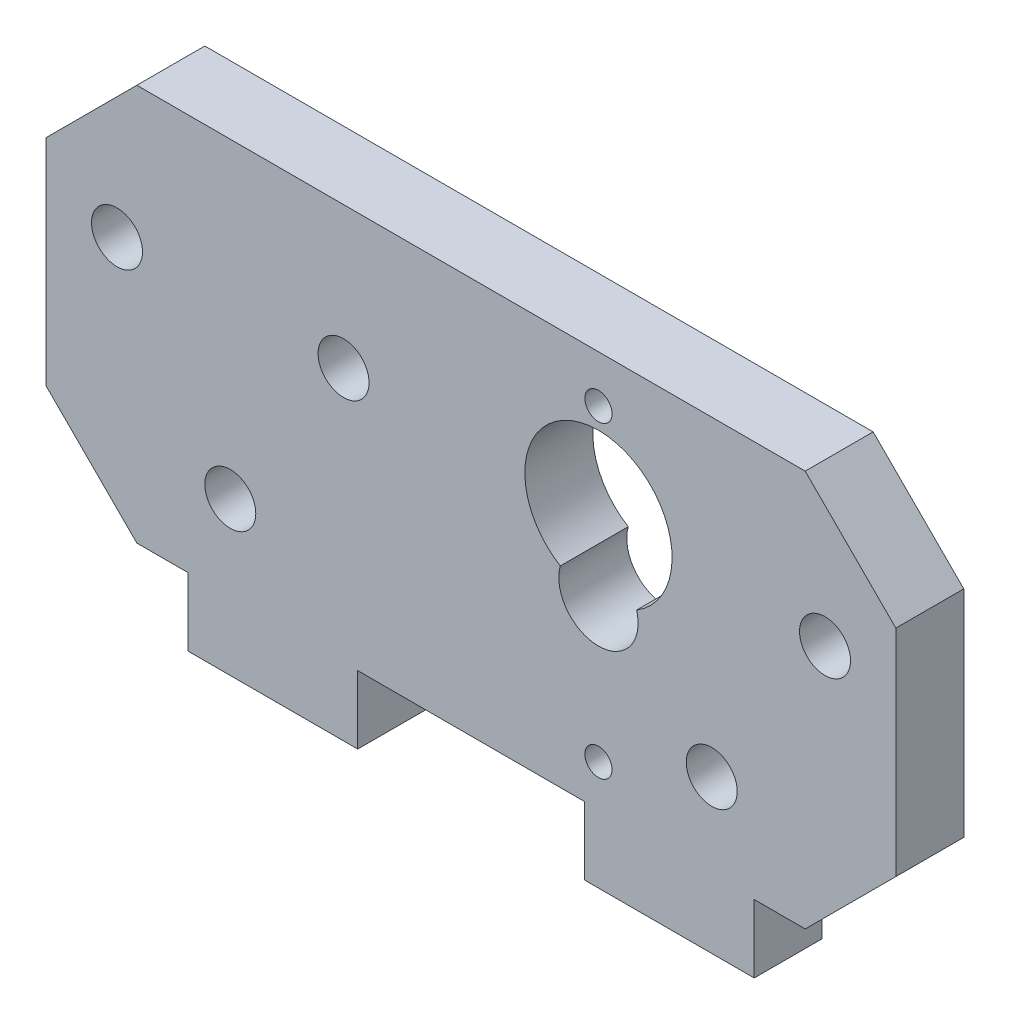
SolidWorks part; units mm, degrees
material "6061-T6 (SS)"
ref_plane "Alzado" through (0, 0, 0) normal (0, 0, 1) x (1, 0, 0)
ref_plane "Planta" through (0, 0, 0) normal (0, 1, 0) x (1, 0, 0)
ref_plane "Vista lateral" through (0, 0, 0) normal (1, 0, 0) x (0, 0, -1)
sketch "Croquis1" plane through (0, 0, 0) normal (0, 0, 1) x (1, 0, 0)
  line L0 (0, 0) -> (0, 17.5) construction
  line L2 (-37.5, 17.5) -> (37.5, 17.5)
  line L3 (-37.5, 17.5) -> (-37.5, -17.5)
  line L4 (-37.5, -17.5) -> (37.5, -17.5)
  line L5 (37.5, 17.5) -> (37.5, -17.5)
  circle A0 centre (11.25, 5) radius 11.25 construction
  arc A1 (14.6208, -0.5577) -> (7.8792, -0.5577) centre (11.25, 5) ccw
  circle A2 centre (-11.25, 5) radius 11.25 construction
  circle A3 centre (-11.25, 5) radius 2.25
  arc A4 (7.8792, -0.5577) -> (14.6208, -0.5577) centre (11.25, -1.5) ccw
  point P11 (0, 17.5)
  point P13 (37.5, 0)
  dimension "D1" = 22.5
  dimension "D2" = 13
  dimension "D6" = 4.5
  dimension "D7" = 7
  dimension "D3" = 35
  dimension "D4" = 75
  dimension "D5" = 5
extrude "Saliente-Extruir1" add sketch "Croquis1" along normal mid plane 6
hole_wizard "Taladro de margen para M41" positions "Croquis2" profile "Croquis3" hole size "M4" standard "Ansi Metric" end condition up to next
sketch "Croquis2" plane through (0, 0, 3) normal (0, 0, 1) x (1, 0, 0)
  line L0 (-31.25, 5) -> (-11.25, 5) construction
  line L2 (11.25, 5) -> (31.25, 5) construction
  arc A0 (14.6208, -0.5577) -> (7.8792, -0.5577) centre (11.25, 5) ccw construction
  circle A1 centre (-11.25, 5) radius 2.25 construction
  point P0 (-31.25, 5)
  point P2 (31.25, 5)
  point P18 (21.25, -10)
  point P20 (-21.25, -10)
  point P23 (-21.25, 5)
  point P25 (21.25, 5)
  dimension "D1" = 20
  dimension "D2" = 15
sketch "Croquis3" plane through (-31.25, 5, 3) normal (1, 0, 0) x (0, -1, 0)
  line L0 (0, 0) -> (0, 6)
  line L1 (0, 6) -> (2.25, 6)
  line L2 (2.25, 6) -> (2.25, 0)
  line L5 (2.25, 0) -> (0, 0)
  line L11 (0, -6.35) -> (0, 107.95) construction
  dimension "Diámetro de taladro hasta el siguiente" = 4.5
  dimension "Profundidad de taladro hasta el siguiente" = 6
hole_wizard "Taladro de margen para M21" positions "Croquis4" profile "Croquis5" hole size "M2" standard "Ansi Metric" end condition up to next
sketch "Croquis4" plane through (0, 0, 3) normal (0, 0, 1) x (1, 0, 0)
  point P0 (11.25, 13.35)
  point P3 (11.25, -13.85)
sketch "Croquis5" plane through (11.25, 13.35, 3) normal (1, 0, 0) x (0, -1, 0)
  line L0 (0, 0) -> (0, 6)
  line L1 (0, 6) -> (1.2, 6)
  line L2 (1.2, 6) -> (1.2, 0)
  line L5 (1.2, 0) -> (0, 0)
  line L11 (0, -6.35) -> (0, 107.95) construction
  dimension "Diámetro de taladro hasta el siguiente" = 2.4
  dimension "Profundidad de taladro hasta el siguiente" = 6
sketch "Croquis6" plane through (0, 0, 3) normal (0, 0, 1) x (1, 0, 0)
  line L0 (-37.5, -17.5) -> (37.5, -17.5) construction
  line L1 (-25, -17.5) -> (-10, -17.5)
  line L2 (-25, -17.5) -> (-25, -23.5)
  line L3 (-25, -23.5) -> (-10, -23.5)
  line L4 (-10, -17.5) -> (-10, -23.5)
  line L5 (-10, -20.5) -> (10, -20.5) construction
  line L6 (10, -17.5) -> (25, -17.5)
  line L7 (10, -17.5) -> (10, -23.5)
  line L8 (10, -23.5) -> (25, -23.5)
  line L9 (25, -17.5) -> (25, -23.5)
  point P12 (0, -20.5)
  dimension "D1" = 15
  dimension "D2" = 20
  dimension "D3" = 6
extrude "Saliente-Extruir2" add sketch "Croquis6" against normal through all
fillet "Redondeo1" radius 8 4 edges at (37.5, -17.5, 0) (-37.5, -17.5, 0) (-37.5, 17.5, 0) (37.5, 17.5, 0) profile chamfer
